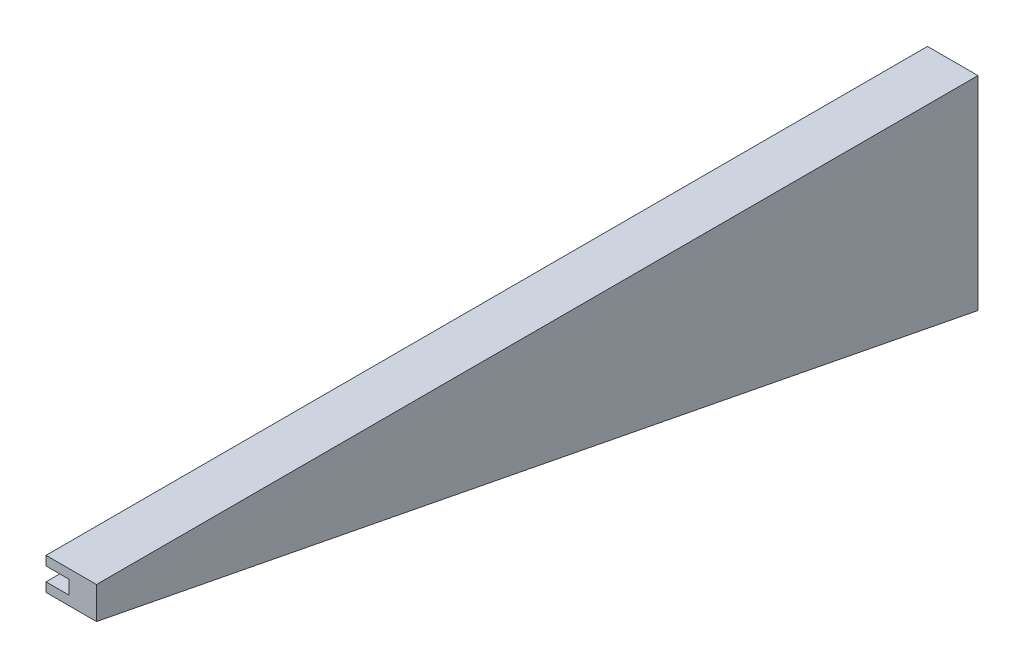
SolidWorks part; units mm, degrees
ref_plane "Front Plane" through (0, 0, 0) normal (0, 0, 1) x (1, 0, 0)
ref_plane "Top Plane" through (0, 0, 0) normal (0, 1, 0) x (1, 0, 0)
ref_plane "Right Plane" through (0, 0, 0) normal (1, 0, 0) x (0, 0, -1)
sketch "Sketch1" plane through (0, 0, 0) normal (0, 0, 1) x (1, 0, 0)
  line L1 (4, -3.5) -> (-4, -3.5)
  line L2 (4, -3.5) -> (4, 3.5)
  line L3 (4, 3.5) -> (-4, 3.5)
  line L4 (-4, -3.5) -> (-4, 3.5)
  line L5 (4, -3.5) -> (-4, 3.5) construction
  line L6 (4, 3.5) -> (-4, -3.5) construction
  point P0 (0, 0)
  dimension "D1" = 8
  dimension "D2" = 7
extrude "Boss-Extrude1" add sketch "Sketch1" along normal blind 192
sketch "Sketch2" plane through (0, 0, 192) normal (0, 0, 1) x (1, 0, 0)
  line L0 (-4, 3.5) -> (-4, -3.5) construction
  line L1 (-4, 1.5) -> (1, 1.5)
  line L2 (-4, 1.5) -> (-4, -1.5)
  line L3 (-4, -1.5) -> (1, -1.5)
  line L4 (1, 1.5) -> (1, -1.5)
  dimension "D1" = 3
  dimension "D2" = 5
extrude "Cut-Extrude1" cut sketch "Sketch2" against normal blind 192
sketch "Sketch3" plane through (4, 0, 0) normal (1, 0, 0) x (0, 0, -1)
  line L0 (-192, -3.5) -> (0, -40.821)
  line L1 (0, -40.821) -> (0, -3.5)
  line L3 (-192, -3.5) -> (0, -3.5) construction
  line L4 (-192, -3.5) -> (-188.4013, -3.5)
  line L7 (0, -3.5) -> (0, 3.5)
  line L8 (0, 3.5) -> (-192, 3.5)
  line L9 (-192, 3.5) -> (-192, -3.5)
  line L10 (-192, -3.5) -> (0, -3.5)
  line L11 (0, -3.5) -> (0, 3.5)
  line L12 (0, 3.5) -> (-192, 3.5)
  line L13 (-192, 3.5) -> (-192, -3.5)
  line L14 (-192, -3.5) -> (-188.4013, -3.5)
  dimension "D1" = 11
  dimension "D2" = 0
extrude "Boss-Extrude2" add sketch "Sketch3" along normal blind 3 contours L0 L1 L11 L12 L13
